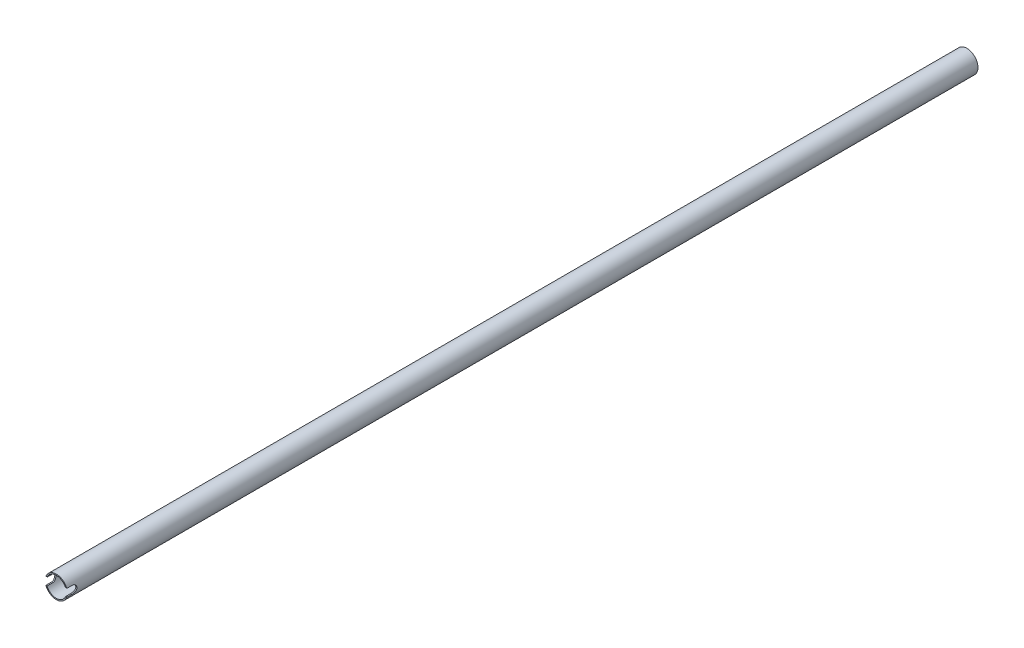
SolidWorks part; units mm, degrees
ref_plane "Front Plane" through (0, 0, 0) normal (0, 0, 1) x (1, 0, 0)
ref_plane "Top Plane" through (0, 0, 0) normal (0, 1, 0) x (1, 0, 0)
ref_plane "Right Plane" through (0, 0, 0) normal (1, 0, 0) x (0, 0, -1)
sketch "Sketch4" plane through (0, 0, 0) normal (0, 0, 1) x (1, 0, 0)
  line L0 (0, 0) -> (58, 0) construction
  circle A0 centre (29, 0) radius 29
  circle A1 centre (29, 0) radius 26
  point P3 (0, 0)
  point P7 (0, 0)
extrude "Boss-Extrude1" add sketch "Sketch4" against normal blind 2380
sketch "Sketch6" plane through (0, 0, 0) normal (1, 0, 0) x (0, 0, -1)
  line L0 (0, 10) -> (0, -10)
  line L1 (0, 29) -> (0, -29) construction
  line L2 (0, -10) -> (15, -10)
  line L3 (0, 10) -> (15, 10)
  arc A0 (15, 10) -> (15, -10) centre (15, 0) cw
  point P6 (0, 0)
extrude "Cut-Extrude1" cut sketch "Sketch6" along normal through all
fillet "Fillet1" radius 1 4 edges at (54.6107, -10, 0) (3.3893, -10, 0) (54.6107, 10, 0) (3.3893, 10, 0)
